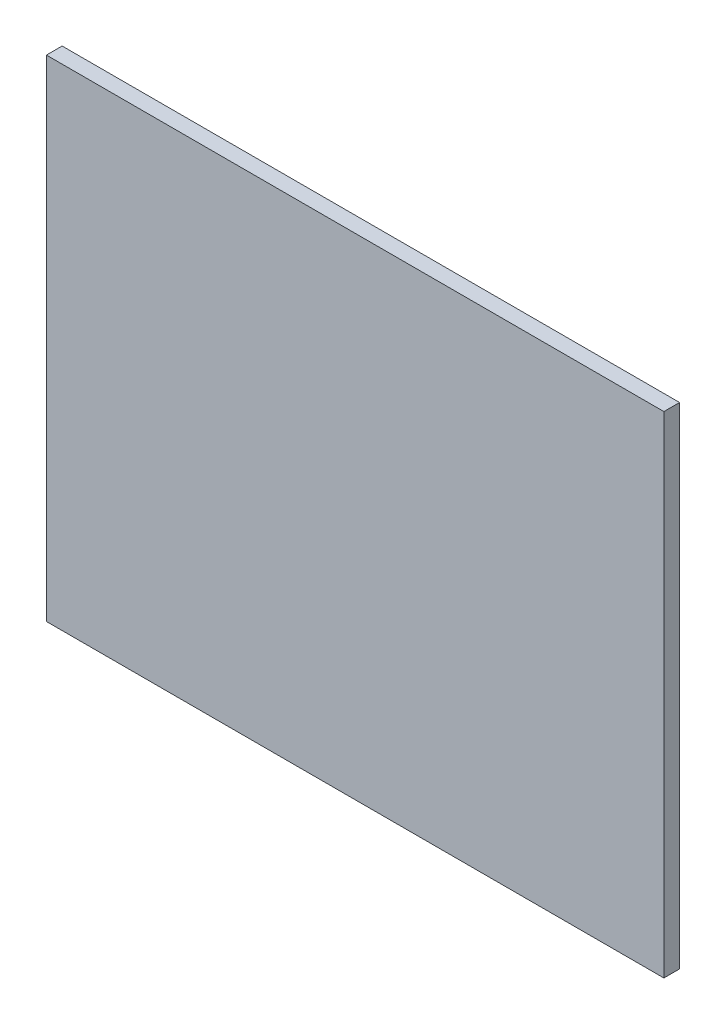
SolidWorks part; units mm, degrees
ref_plane "Alzado" through (0, 0, 0) normal (0, 0, 1) x (1, 0, 0)
ref_plane "Planta" through (0, 0, 0) normal (0, 1, 0) x (1, 0, 0)
ref_plane "Vista lateral" through (0, 0, 0) normal (1, 0, 0) x (0, 0, -1)
sketch "Croquis1" plane through (0, 0, 0) normal (0, 0, 1) x (1, 0, 0)
  line L0 (0, 215.0467) -> (0, -209.8802) construction
  line L1 (-236, -187.5) -> (236, -187.5)
  line L2 (-236, -187.5) -> (-236, 187.5)
  line L3 (-236, 187.5) -> (236, 187.5)
  line L4 (236, -187.5) -> (236, 187.5)
  line L5 (-236, -187.5) -> (236, 187.5) construction
  line L6 (-236, 187.5) -> (236, -187.5) construction
  line L7 (-264.2115, 0) -> (260.4911, 0) construction
  point P0 (0, 0)
  dimension "D1" = 375
  dimension "D2" = 472
extrude "Saliente-Extruir1" add sketch "Croquis1" along normal mid plane 12
sketch "Croquis2" plane through (0, 0, 0) normal (0, 0, 1) x (1, 0, 0)
  line L6 (0, 203.0536) -> (0, -187.5) construction
  line L7 (-236, -187.5) -> (236, -187.5) construction
  line L8 (-230, 0) -> (230, 0) construction
  line L9 (-230, 181.5) -> (-230, -187.5)
  line L10 (230, -187.5) -> (230, 181.5)
  line L11 (230, 181.5) -> (-230, 181.5)
  line L12 (-230, 181.5) -> (-230, -187.5) construction
  line L13 (230, -187.5) -> (230, 181.5) construction
  line L14 (230, 181.5) -> (-230, 181.5) construction
  line L16 (-230, 181.5) -> (-182.713, 181.5) construction
  line L17 (-230, 181.5) -> (-230, 140) construction
  line L18 (-230, 140) -> (-182.713, 140) construction
  line L19 (-182.713, 181.5) -> (-182.713, 140) construction
  circle A1 centre (-230, 70) radius 3
  circle A2 centre (-230, 140) radius 3
  circle A3 centre (-182.713, 181.5) radius 3
  circle A4 centre (-92.713, 181.5) radius 3
  circle A5 centre (92.713, 181.5) radius 3
  circle A6 centre (182.713, 181.5) radius 3
  circle A7 centre (-230, -140) radius 3
  circle A8 centre (-230, -70) radius 3
  circle A9 centre (230, -140) radius 3
  circle A10 centre (230, -70) radius 3
  circle A11 centre (230, 70) radius 3
  circle A12 centre (230, 140) radius 3
  dimension "D3" = 2
  dimension "D1" = 6
extrude "Cortar-Extruir1" cut sketch "Croquis2" against normal blind 12
